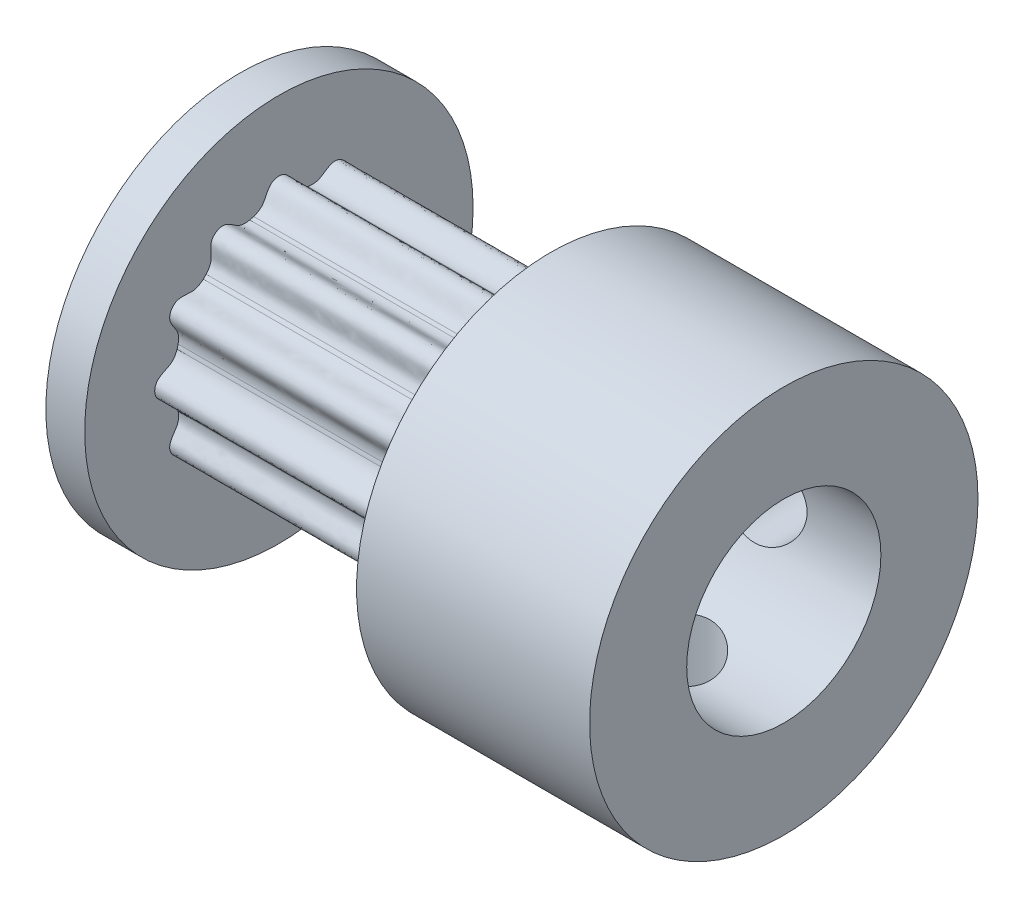
SolidWorks part; units mm, degrees
material "6063-T5"
ref_plane "Спереди" through (0, 0, 0) normal (0, 0, 1) x (1, 0, 0)
ref_plane "Сверху" through (0, 0, 0) normal (0, 1, 0) x (1, 0, 0)
ref_plane "Справа" through (0, 0, 0) normal (1, 0, 0) x (0, 0, -1)
sketch "Sketch1" plane through (0, 0, 0) normal (0, 1, 0) x (1, 0, 0)
  line L0 (0, 0) -> (-14, 0) construction
  line L1 (0, 2.5) -> (-14, 2.5)
  line L2 (-14, 2.5) -> (-14, 5)
  line L3 (-14, 5) -> (-13, 5)
  line L4 (-13, 5) -> (-13, 2.7)
  line L5 (-13, 2.7) -> (-6, 2.7)
  line L6 (-6, 2.7) -> (-6, 5)
  line L7 (-6, 5) -> (0, 5)
  line L8 (0, 5) -> (0, 2.5)
  dimension "D1" = 14
  dimension "D2" = 10
  dimension "D3" = 5
  dimension "D4" = 1
  dimension "D5" = 5.4
  dimension "D6" = 6
revolve "Base" add sketch "Sketch1" angle 360 about L0
sketch "Sketch2" plane through (-14, 0, 0) normal (-1, 0, 0) x (0, 0, 1)
  line L0 (0, 0) -> (0, 5.8) construction
  line L1 (0, 0) -> (-1.5541, 5.8) construction
  line L2 (0, 0) -> (1.5541, 5.8) construction
  line L6 (0, 0) -> (-0.7636, 5.8) construction
  circle A0 centre (0, 0) radius 3.2 construction
  arc A1 (-0.698, 2.605) -> (0.698, 2.605) centre (0, 0.088) cw
  circle A14 centre (0, 0) radius 2.7 construction
  spline S0 degree 3 poles (-0.698, 2.605) (-0.5791, 2.6401) (-0.4329, 2.7095) (-0.2648, 3.077) (-0.1835, 3.1877) (0, 3.2) knots 0 0 0 0 0.181357 0.234422 0.530653 0.530653 0.530653 0.530653 construction
  spline S1 degree 3 poles (0.698, 2.605) (0.5791, 2.6401) (0.4329, 2.7095) (0.2648, 3.077) (0.1835, 3.1877) (0, 3.2) knots 0 0 0 0 0.181357 0.234422 0.530653 0.530653 0.530653 0.530653 construction
  spline S2 degree 3 poles (-0.698, 2.605) (-0.5791, 2.6401) (-0.4329, 2.7095) (-0.2933, 3.0148) (-0.2272, 3.1221) (-0.1391, 3.166) (-0.1114, 3.1798) (-0.0514, 3.1979) (0.0514, 3.1979) (0.1114, 3.1798) (0.1391, 3.166) (0.2272, 3.1221) (0.2933, 3.0148) (0.4329, 2.7095) (0.5791, 2.6401) (0.698, 2.605) knots 0 0 0 0 0.168536 0.217849 0.409697 0.409697 0.409697 0.469899 0.530101 0.590303 0.590303 0.590303 0.782151 0.831464 1 1 1 1
  point P72 (0, 0)
  point P98 (0, 0)
  dimension "D1" = 6.4
  dimension "D6" = 12
  dimension "D7" = 5.4
  dimension "D2" = 30
  dimension "D3" = 5.8
  dimension "D4" = 15
  dimension "D5" = 7.5
extrude "Tooth" add sketch "Sketch2" against normal blind 9
pattern_circular "Teeth" count 12 over 360 about axis through (0, 0, 0) along (1, 0, 0) of "Tooth"
sketch "Sketch3" plane through (0, 0, 0) normal (0, 0, 1) x (1, 0, 0)
  line L0 (0, -5) -> (0, 5) construction
  circle A0 centre (-3, 0) radius 1.1
  dimension "D1" = 2.2
  dimension "D2" = 3
extrude "SetScrewHole1" cut sketch "Sketch3" against normal blind 6
cosmetic thread "Cosmetic Thread1" parameters "D2"=3
sketch "Sketch4" plane through (0, 0, 0) normal (0, 1, 0) x (1, 0, 0)
  line L0 (0, -5) -> (0, 5) construction
  circle A0 centre (-3, 0) radius 1.1
  dimension "D1" = 3
  dimension "D2" = 2.2
extrude "SetScrewHole2" cut sketch "Sketch4" against normal blind 6
cosmetic thread "Cosmetic Thread2" parameters "D2"=3
